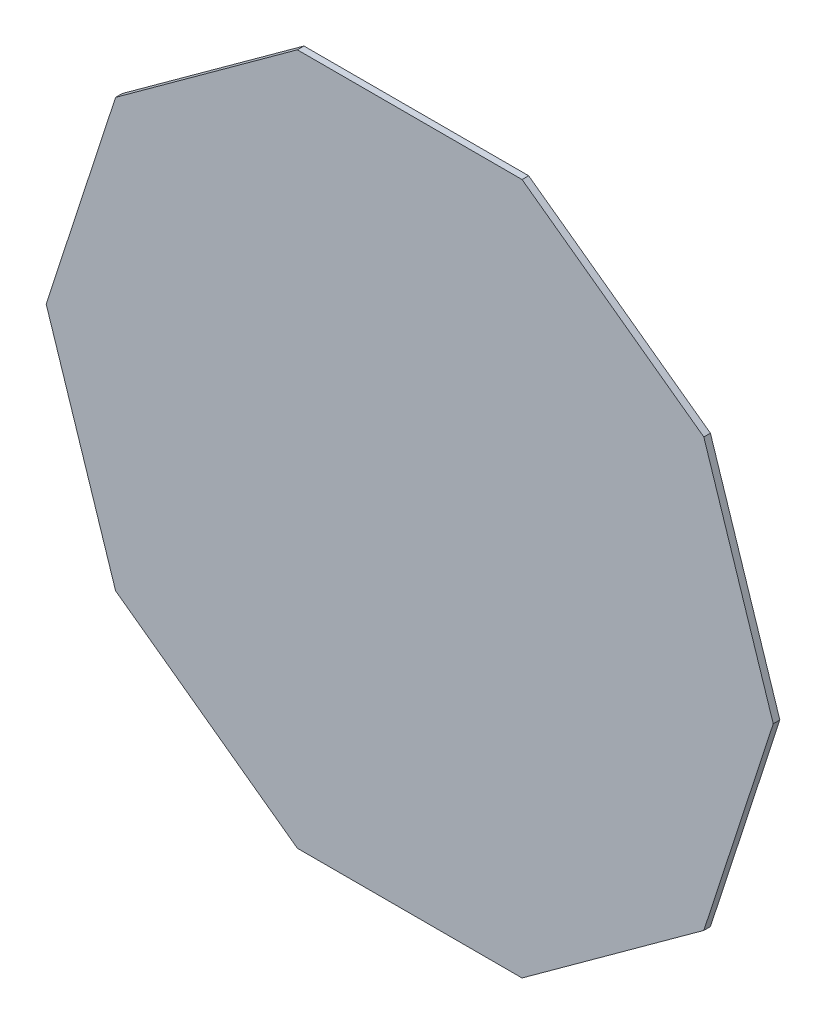
SolidWorks part; units mm, degrees
ref_plane "Front Plane" through (0, 0, 0) normal (0, 0, 1) x (1, 0, 0)
ref_plane "Top Plane" through (0, 0, 0) normal (0, 1, 0) x (1, 0, 0)
ref_plane "Right Plane" through (0, 0, 0) normal (1, 0, 0) x (0, 0, -1)
sketch "Sketch1" plane through (0, 0, 0) normal (0, 0, 1) x (1, 0, 0)
  line L1 (6308.7733, 0) -> (5103.9049, 3708.2039)
  line L2 (5103.9049, 3708.2039) -> (1949.5182, 6000)
  line L3 (1949.5182, 6000) -> (-1949.5182, 6000)
  line L4 (-1949.5182, 6000) -> (-5103.9049, 3708.2039)
  line L5 (-5103.9049, 3708.2039) -> (-6308.7733, 0)
  line L6 (-6308.7733, 0) -> (-5103.9049, -3708.2039)
  line L7 (-5103.9049, -3708.2039) -> (-1949.5182, -6000)
  line L8 (-1949.5182, -6000) -> (1949.5182, -6000)
  line L9 (1949.5182, -6000) -> (5103.9049, -3708.2039)
  line L10 (5103.9049, -3708.2039) -> (6308.7733, 0)
  circle A0 centre (0, 0) radius 6000 construction
  dimension "D1" = 12000
extrude "Boss-Extrude1" add sketch "Sketch1" along normal blind 114.3
